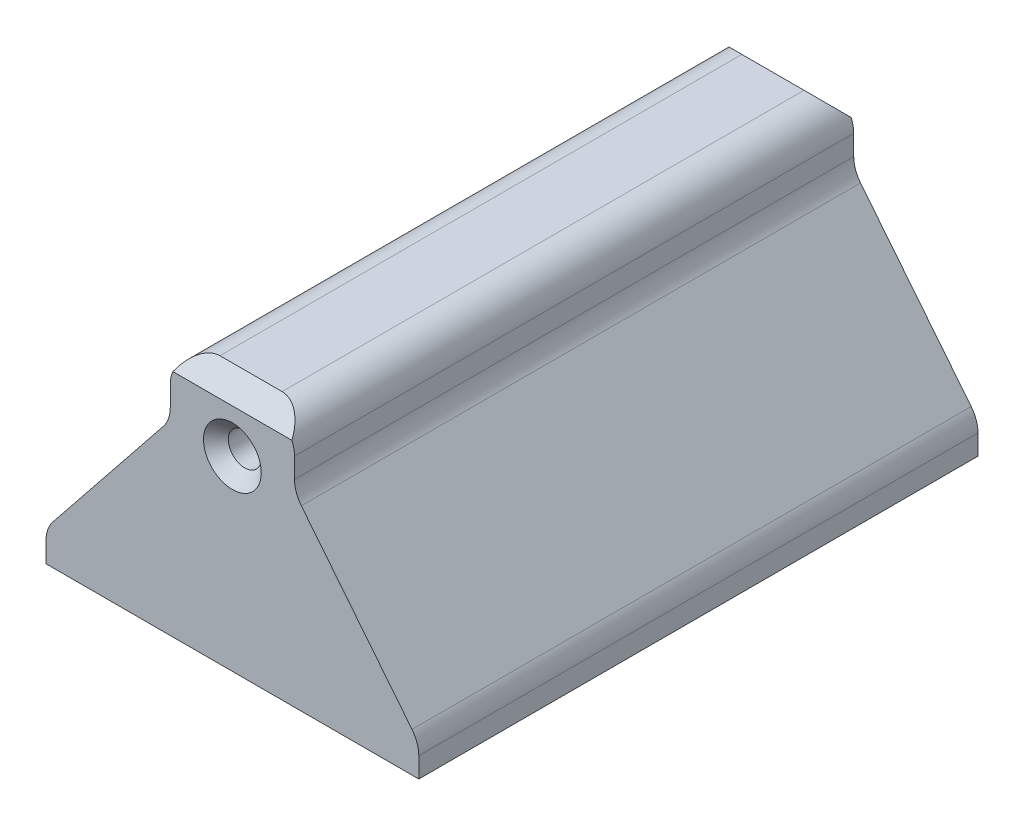
SolidWorks part; units mm, degrees
ref_plane "Front Plane" through (0, 0, 0) normal (0, 0, 1) x (1, 0, 0)
ref_plane "Top Plane" through (0, 0, 0) normal (0, 1, 0) x (1, 0, 0)
ref_plane "Right Plane" through (0, 0, 0) normal (1, 0, 0) x (0, 0, -1)
sketch "Sketch1" plane through (0, 0, 0) normal (1, 0, 0) x (0, 0, -1)
  line L9 (0, 0) -> (-114.3, 0)
  line L10 (0, 0) -> (0, -50.8)
  line L11 (0, -50.8) -> (-114.3, -50.8)
  line L12 (-114.3, 0) -> (-114.3, -50.8)
  dimension "D1" = 50.8
  dimension "D2" = 114.3
extrude "Boss-Extrude1" add sketch "Sketch1" along normal blind 25.4
sketch "Sketch2" plane through (0, 0, 0) normal (0, 0, -1) x (-1, 0, 0)
  line L0 (-25.4, 0) -> (0, 0) construction
  circle A0 centre (-12.7, -12.7) radius 3.3655
  point P4 (-12.7, 0)
  dimension "D2" = 6.731
  dimension "D1" = 12.7
extrude "Cut-Extrude1" cut sketch "Sketch2" against normal through all
chamfer "Chamfer1" distance 2.54 angle 45 2 edges at (12.7, -9.3345, 114.3) (12.7, -9.3345, 0)
sketch "Sketch3" plane through (0, 0, 0) normal (0, 0, -1) x (-1, 0, 0)
  line L0 (-12.7, 0) -> (-12.7, -50.8) construction
  line L1 (-25.4, 0) -> (0, 0) construction
  line L2 (-25.4, -50.8) -> (0, -50.8) construction
  line L3 (-50.8, -44.45) -> (-25.4, -12.7)
  line L4 (-25.4, -50.8) -> (-50.8, -50.8)
  line L5 (-25.4, -50.8) -> (-25.4, -12.7)
  line L7 (-50.8, -50.8) -> (-50.8, -44.45)
  line L8 (-25.4, -50.8) -> (-25.4, 0) construction
  line L9 (25.4, -50.8) -> (25.4, -44.45)
  line L10 (0, -50.8) -> (0, -12.7)
  line L11 (0, -50.8) -> (25.4, -50.8)
  line L12 (25.4, -44.45) -> (0, -12.7)
  dimension "D1" = 6.35
  dimension "D2" = 38.1
  dimension "D3" = 25.4
extrude "Boss-Extrude2" add sketch "Sketch3" against normal up to surface (114.3 mm away) up to face at (12.7, -6.7945, 114.3)
chamfer "Chamfer2" distance 3.81 angle 45 2 edges at (12.7, 0, 114.3) (12.7, 0, 0)
fillet "Fillet1" radius 6.35 6 edges at (-25.4, -44.45, 57.15) (0, -12.7, 57.15) (0, 0, 57.15) (25.4, 0, 57.15) (50.8, -44.45, 57.15) (25.4, -12.7, 57.15)
